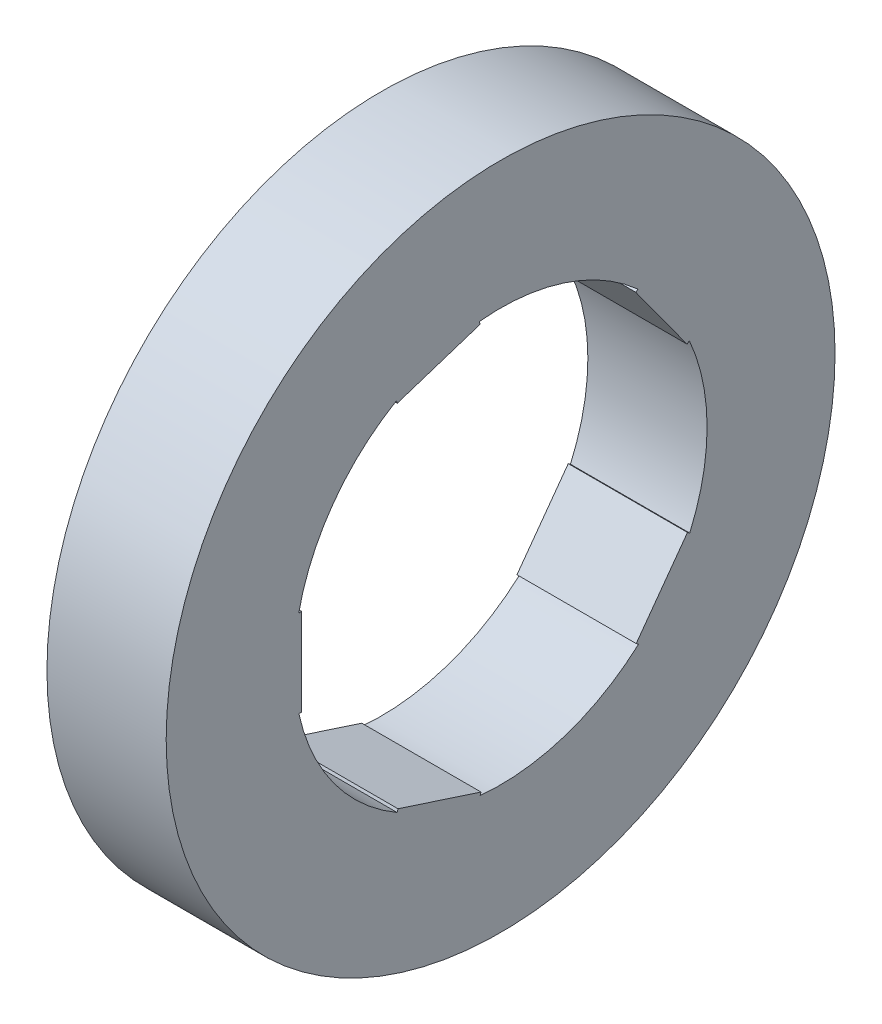
SolidWorks part; units mm, degrees
material "PVC hart"
ref_plane "Ebene vorne" through (0, 0, 0) normal (0, 0, 1) x (1, 0, 0)
ref_plane "Ebene oben" through (0, 0, 0) normal (0, 1, 0) x (1, 0, 0)
ref_plane "Ebene rechts" through (0, 0, 0) normal (1, 0, 0) x (0, 0, -1)
sketch "Skizze1" plane through (0, 0, 0) normal (1, 0, 0) x (0, 0, -1)
  circle A0 centre (0, 0) radius 11.5
  dimension "D1" = 23
extrude "Aufsatz-Linear austragen1" add sketch "Skizze1" along normal blind 77
sketch "Skizze2" plane through (77, 0, 0) normal (1, 0, 0) x (0, 0, -1)
  line L0 (-15.3822, 0) -> (15.9559, 0) construction
  line L1 (-6.9427, 1.4864) -> (-6.8427, 1.4864)
  line L2 (-6.8427, 1.4864) -> (-6.8427, -1.5136)
  line L3 (-6.8427, -1.5136) -> (-6.9368, -1.5136)
  line L4 (-0.7318, 7.0622) -> (-0.7009, 6.9671)
  line L5 (-0.7009, 6.9671) -> (-3.554, 6.04)
  line L6 (-3.554, 6.04) -> (-3.5831, 6.1295)
  line L7 (6.4904, 2.8783) -> (6.4095, 2.8195)
  line L8 (6.4095, 2.8195) -> (4.6462, 5.2466)
  line L9 (4.6462, 5.2466) -> (4.7223, 5.3019)
  line L10 (4.7431, -5.2833) -> (4.6622, -5.2245)
  line L11 (4.6622, -5.2245) -> (6.4255, -2.7975)
  line L12 (6.4255, -2.7975) -> (6.5017, -2.8528)
  line L13 (-3.559, -6.1436) -> (-3.5281, -6.0484)
  line L14 (-3.5281, -6.0484) -> (-0.675, -6.9755)
  line L15 (-0.675, -6.9755) -> (-0.7041, -7.065)
  arc A0 (-6.9368, -1.5136) -> (-3.559, -6.1436) centre (0, 0) ccw
  arc A1 (-3.5831, 6.1295) -> (-6.9427, 1.4864) centre (0, 0) ccw
  arc A2 (4.7223, 5.3019) -> (-0.7318, 7.0622) centre (0, 0) ccw
  arc A3 (6.5017, -2.8528) -> (6.4904, 2.8783) centre (0, 0) ccw
  arc A4 (-0.7041, -7.065) -> (4.7431, -5.2833) centre (0, 0) ccw
  point P28 (0, 0)
  dimension "D1" = 14.2
  dimension "D2" = 3
  dimension "D3" = 0.1
  dimension "D4" = 5
extrude "Schnitt-Linear austragen1" cut sketch "Skizze2" against normal blind 4.1
sketch "Skizze3" plane through (72.9, 0, 0) normal (1, 0, 0) x (0, 0, -1)
  circle A0 centre (0, 0) radius 2.1
  dimension "D1" = 4.2
extrude "Schnitt-Linear austragen2" cut sketch "Skizze3" against normal blind 3
sketch "Skizze4" plane through (0, 0, 0) normal (-1, 0, 0) x (0, 0, 1)
  circle A0 centre (0, 0) radius 9.6
  dimension "D1" = 19.2
extrude "Schnitt-Linear austragen3" cut sketch "Skizze4" against normal blind 12.75
sketch "Skizze7" plane through (77, 0, 0) normal (1, 0, 0) x (0, 0, -1)
  line L0 (0, 13.4409) -> (0, -14.2481) construction
  line L1 (-11.5, 7.5) -> (-10, 7.5)
  line L2 (-11.5, 7.5) -> (-11.5, -7.5)
  line L3 (-11.5, -7.5) -> (-10, -7.5)
  line L4 (-10, 7.5) -> (-10, -7.5)
  dimension "D1" = 1.5
  dimension "D2" = 15
  dimension "D3" = 10
extrude "Schnitt-Linear austragen4" cut sketch "Skizze7" against normal blind 63 from offset 6 offset against normal yes
sketch "Skizze8" plane through (0, 0, 10) normal (0, 0, 1) x (1, 0, 0)
  line L0 (71, -5.6789) -> (71, 5.6789) construction
  line L1 (8, 2) -> (71, 2)
  line L2 (8, 2) -> (8, -2)
  line L3 (8, -2) -> (71, -2)
  line L4 (71, 2) -> (71, -2)
  line L5 (8, 2) -> (71, -2) construction
  line L6 (8, -2) -> (71, 2) construction
  line L7 (12.65, 0) -> (-12.65, 0) construction
  point P0 (39.5, 0)
  dimension "D1" = 31.5
  dimension "D3" = 63
  dimension "D4" = 4
extrude "Aufsatz-Linear austragen2" add sketch "Skizze8" along normal blind 1.5
sketch "Skizze10" plane through (12.75, 0, 0) normal (-1, 0, 0) x (0, 0, 1)
  line L1 (4.0389, -2.2407) -> (3.96, 2.3774)
  line L2 (3.96, 2.3774) -> (-0.0789, 4.6181)
  line L3 (-0.0789, 4.6181) -> (-4.0389, 2.2407)
  line L4 (-4.0389, 2.2407) -> (-3.96, -2.3774)
  line L5 (-3.96, -2.3774) -> (0.0789, -4.6181)
  line L6 (0.0789, -4.6181) -> (4.0389, -2.2407)
  circle A0 centre (0, 0) radius 4 construction
  dimension "D1" = 8
extrude "Schnitt-Linear austragen6" cut sketch "Skizze10" against normal blind 13.5
sketch "Skizze12" plane through (26.25, 0, 0) normal (-1, 0, 0) x (0, 0, 1)
  circle A0 centre (0, 0) radius 3
  dimension "D1" = 6
extrude "Schnitt-Linear austragen7" cut sketch "Skizze12" against normal blind 2
pattern_circular "Kreismuster3" count 3 over 360 about axis through (0, 0, 0) along (1, 0, 0) of "Aufsatz-Linear austragen2", "Schnitt-Linear austragen4"
sketch "Skizze13" plane through (69.9, 0, 0) normal (1, 0, 0) x (0, 0, -1)
  circle A0 centre (0, 0) radius 8.5
extrude "Schnitt-Linear austragen8" cut sketch "Skizze13" against normal blind 40
sketch "Skizze15" plane through (0, 0, 0) normal (-1, 0, 0) x (0, 0, 1)
  circle A0 centre (0, 0) radius 14.3369
extrude "Schnitt-Linear austragen10" cut sketch "Skizze15" against normal blind 72.9
